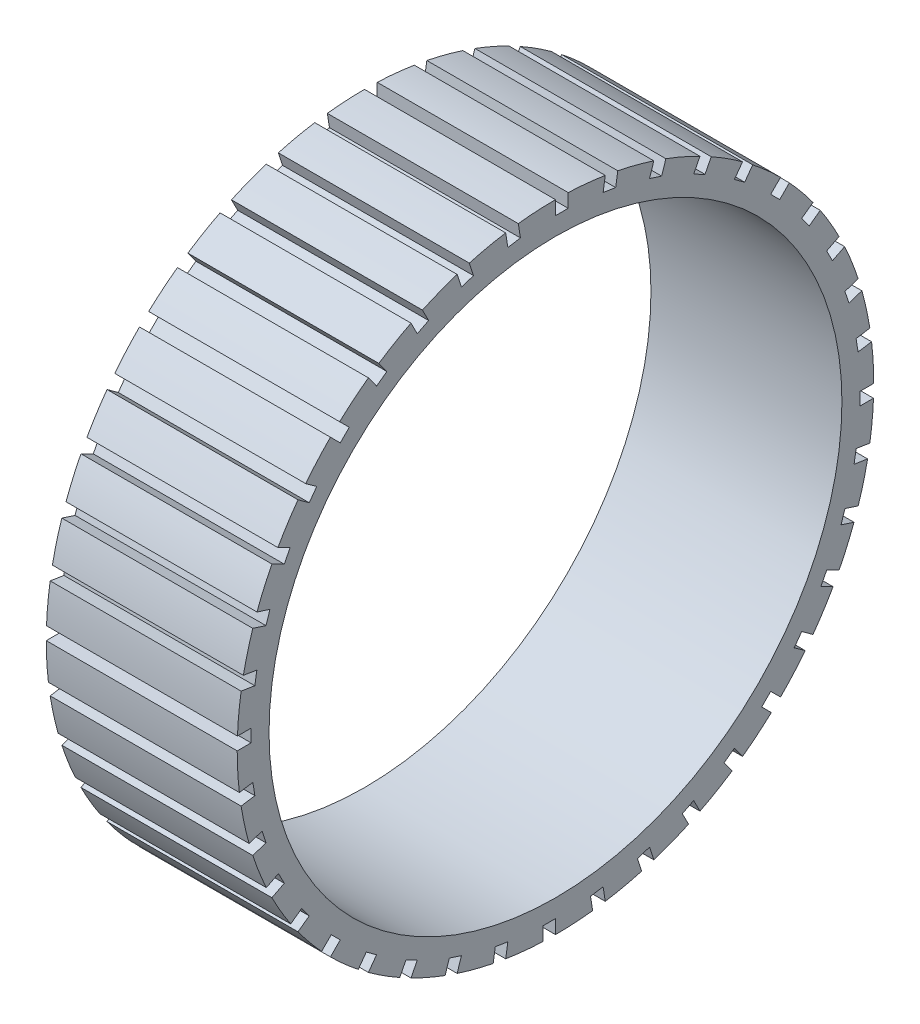
SolidWorks part; units mm, degrees
material "Rubber"
ref_plane "Front Plane" through (0, 0, 0) normal (0, 0, 1) x (1, 0, 0)
ref_plane "Top Plane" through (0, 0, 0) normal (0, 1, 0) x (1, 0, 0)
ref_plane "Right Plane" through (0, 0, 0) normal (1, 0, 0) x (0, 0, -1)
sketch "Sketch1" plane through (0, 0, 0) normal (1, 0, 0) x (0, 0, -1)
  circle A0 centre (0, 0) radius 63.5
  dimension "D1" = 127
extrude "Boss-Extrude1" add sketch "Sketch1" along normal blind 38.1
sketch "Sketch2" plane through (0, 0, 0) normal (1, 0, 0) x (0, 0, -1)
  circle A0 centre (0, 0) radius 57.15
extrude "Cut-Extrude4" cut sketch "Sketch2" along normal blind 40.64
sketch "Sketch4" plane through (0, 0, 0) normal (-1, 0, 0) x (0, 0, 1)
  line L1 (-63.5, 0) -> (-60.727, 0)
  line L2 (-63.5, 0) -> (-63.5, -2.54)
  line L3 (-63.5, -2.54) -> (-60.727, -2.54)
  line L4 (-60.727, 0) -> (-60.727, -2.54)
  circle A0 centre (0, 0) radius 63.5 construction
extrude "Cut-Extrude7" cut sketch "Sketch4" against normal blind 40.64
pattern_circular "CirPattern1" count 40 over 360 about axis through (0, 0, 0) along (1, 0, 0) of "Cut-Extrude7"
